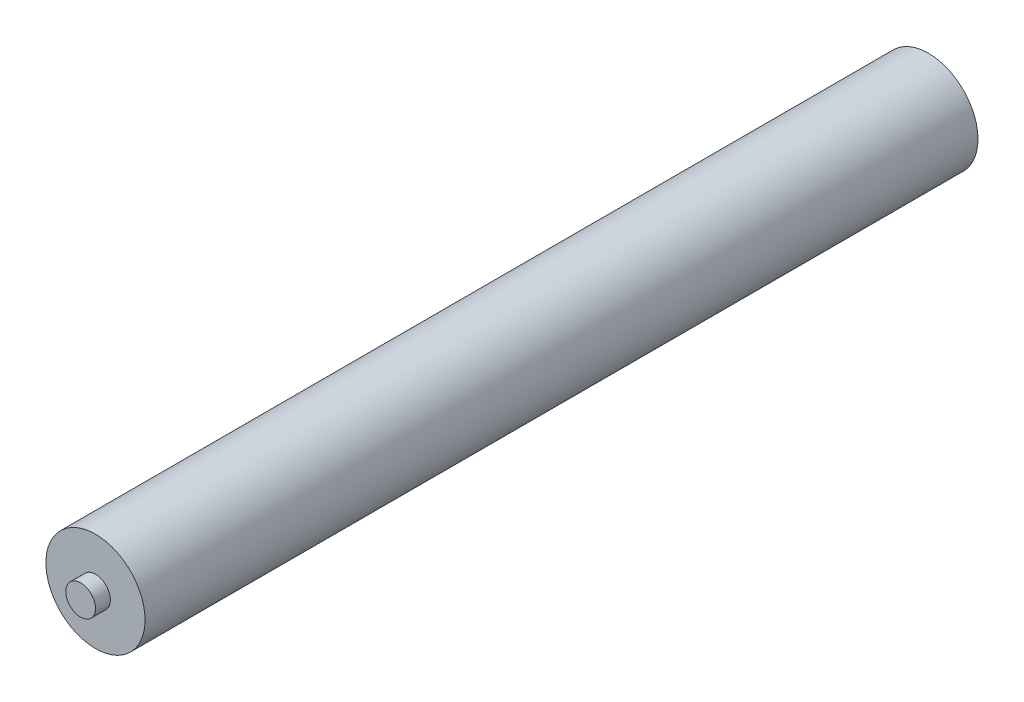
SolidWorks part; units mm, degrees
ref_plane "Front Plane" through (0, 0, 0) normal (0, 0, 1) x (1, 0, 0)
ref_plane "Top Plane" through (0, 0, 0) normal (0, 1, 0) x (1, 0, 0)
ref_plane "Right Plane" through (0, 0, 0) normal (1, 0, 0) x (0, 0, -1)
sketch "Sketch1" plane through (0, 0, 0) normal (0, 0, 1) x (1, 0, 0)
  circle A0 centre (0, 0) radius 50
extrude "Boss-Extrude1" add sketch "Sketch1" along normal mid plane 840
sketch "Sketch3" plane through (0, 0, 0) normal (0, 0, 1) x (1, 0, 0)
  circle A0 centre (0, 0) radius 15
extrude "Boss-Extrude3" add sketch "Sketch3" along normal mid plane 870
